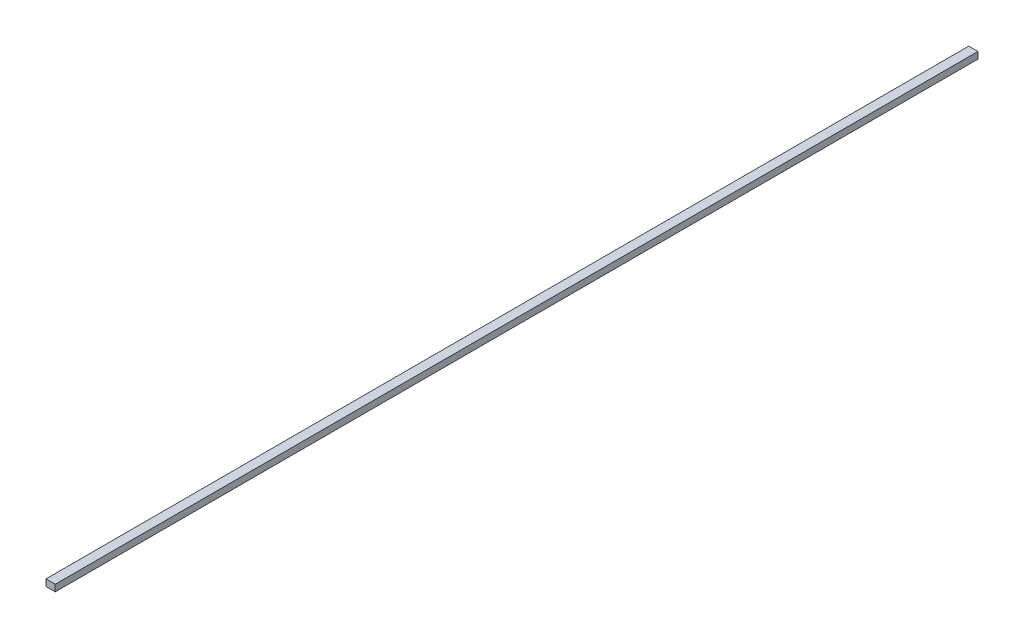
SolidWorks part; units mm, degrees
ref_plane "Front Plane" through (0, 0, 0) normal (0, 0, 1) x (1, 0, 0)
ref_plane "Top Plane" through (0, 0, 0) normal (0, 1, 0) x (1, 0, 0)
ref_plane "Right Plane" through (0, 0, 0) normal (1, 0, 0) x (0, 0, -1)
sketch "Sketch2" plane through (0, 0, 0) normal (0, 0, 1) x (1, 0, 0)
  line L1 (0, 0) -> (5, 0)
  line L2 (0, 0) -> (0, 3.6)
  line L3 (0, 3.6) -> (5, 3.6)
  line L4 (5, 0) -> (5, 3.6)
  dimension "D1" = 3.6
  dimension "D2" = 5
extrude "Boss-Extrude1" add sketch "Sketch2" along normal blind 500
